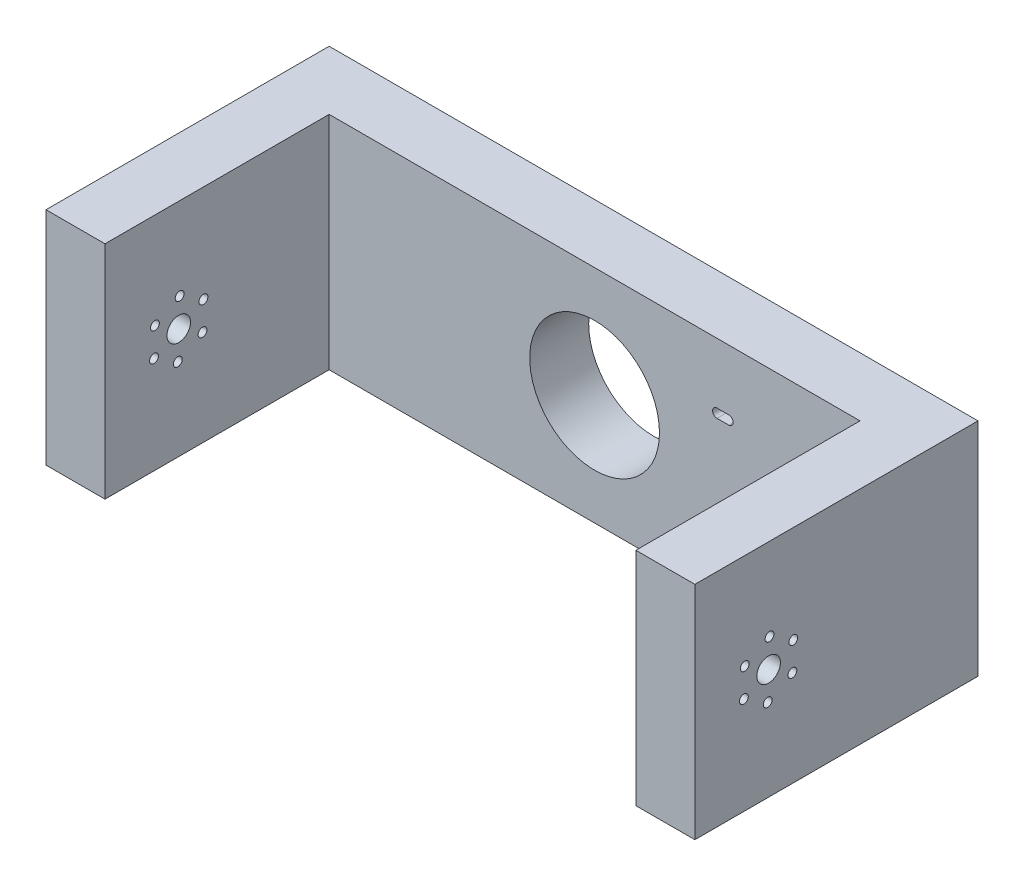
SolidWorks part; units mm, degrees
ref_plane "Front" through (0, 0, 0) normal (0, 0, 1) x (1, 0, 0)
ref_plane "Top" through (0, 0, 0) normal (0, 1, 0) x (1, 0, 0)
ref_plane "Right" through (0, 0, 0) normal (1, 0, 0) x (0, 0, -1)
sketch "Esquisse1" plane through (0, 0, 0) normal (0, 0, 1) x (1, 0, 0)
  line L1 (0, 0) -> (220, 0)
  line L2 (0, 0) -> (0, 75)
  line L3 (0, 75) -> (220, 75)
  line L4 (220, 0) -> (220, 75)
  dimension "D1" = 220
  dimension "D2" = 75
extrude "Boss.-Extru.1" add sketch "Esquisse1" along normal blind 20
sketch "Esquisse2" plane through (0, 0, 20) normal (0, 0, 1) x (1, 0, 0)
  line L0 (0, 0) -> (220, 0) construction
  line L1 (220, 75) -> (200, 75)
  line L2 (220, 75) -> (220, 0)
  line L3 (220, 0) -> (200, 0)
  line L4 (200, 75) -> (200, 0)
  line L6 (0, 75) -> (20, 75)
  line L7 (0, 75) -> (0, 0)
  line L8 (0, 0) -> (20, 0)
  line L9 (20, 75) -> (20, 0)
  dimension "D1" = 20
extrude "Boss.-Extru.2" add sketch "Esquisse2" along normal blind 76
sketch "Esquisse3" plane through (220, 0, 0) normal (1, 0, 0) x (0, 0, -1)
  line L0 (-96, 0) -> (-96, 75) construction
  line L1 (-96, 75) -> (0, 75) construction
  circle A0 centre (-71, 37.5) radius 4
  dimension "D1" = 8
  dimension "D2" = 25
  dimension "D3" = 37.5
extrude "Enlèv. mat.-Extru.1" cut sketch "Esquisse3" against normal through all
sketch "Esquisse4" plane through (0, 0, 20) normal (0, 0, 1) x (1, 0, 0)
  line L0 (220, 0) -> (220, 75) construction
  line L2 (200, 75) -> (20, 75) construction
  circle A0 centre (110, 37.5) radius 22
  dimension "D1" = 110
  dimension "D2" = 37.5
  dimension "D3" = 44
extrude "Enlèv. mat.-Extru.2" cut sketch "Esquisse4" against normal blind 76
sketch "Esquisse5" plane through (220, 0, 0) normal (1, 0, 0) x (0, 0, -1)
  circle A0 centre (-70.6855, 47) radius 1.5
  circle A1 centre (-71, 37.5) radius 4 construction
  circle A2 centre (-62.6155, 41.9776) radius 1.5
  circle A3 centre (-62.93, 32.4776) radius 1.5
  circle A4 centre (-71.3145, 28) radius 1.5
  circle A5 centre (-79.3845, 33.0224) radius 1.5
  circle A6 centre (-79.07, 42.5224) radius 1.5
  point P17 (-71, 37.5)
  dimension "D1" = 3
  dimension "D2" = 9.5
  dimension "D3" = 6
extrude "Enlèv. mat.-Extru.3" cut sketch "Esquisse5" against normal through all
sketch "Esquisse6" plane through (0, 0, 20) normal (0, 0, 1) x (1, 0, 0)
  line L0 (200, 75) -> (20, 75) construction
  line L1 (148, 58.5) -> (190, 58.5)
  line L2 (148, 58.5) -> (148, 16.5)
  line L3 (148, 16.5) -> (190, 16.5)
  line L4 (190, 58.5) -> (190, 16.5)
  line L5 (200, 75) -> (200, 0) construction
  line L6 (182.5, 53) -> (186.5, 53) construction
  line L9 (182.5, 54.5) -> (186.5, 54.5)
  line L10 (182.5, 51.5) -> (186.5, 51.5)
  line L11 (151.5, 51.5) -> (155.5, 51.5)
  line L12 (151.5, 54.5) -> (155.5, 54.5)
  line L13 (151.5, 53) -> (155.5, 53) construction
  line L14 (151.5, 20.5) -> (155.5, 20.5)
  line L15 (151.5, 23.5) -> (155.5, 23.5)
  line L16 (151.5, 22) -> (155.5, 22) construction
  line L17 (182.5, 20.5) -> (186.5, 20.5)
  line L18 (182.5, 23.5) -> (186.5, 23.5)
  line L19 (182.5, 22) -> (186.5, 22) construction
  circle A0 centre (153.5, 53) radius 1.5
  circle A1 centre (184.5, 53) radius 1.5
  circle A2 centre (184.5, 22) radius 1.5
  circle A3 centre (153.5, 22) radius 1.5
  arc A6 (182.5, 54.5) -> (182.5, 51.5) centre (182.5, 53) ccw
  arc A7 (186.5, 51.5) -> (186.5, 54.5) centre (186.5, 53) ccw
  arc A8 (151.5, 54.5) -> (151.5, 51.5) centre (151.5, 53) ccw
  arc A9 (155.5, 51.5) -> (155.5, 54.5) centre (155.5, 53) ccw
  arc A10 (151.5, 23.5) -> (151.5, 20.5) centre (151.5, 22) ccw
  arc A11 (155.5, 20.5) -> (155.5, 23.5) centre (155.5, 22) ccw
  arc A12 (182.5, 23.5) -> (182.5, 20.5) centre (182.5, 22) ccw
  arc A13 (186.5, 20.5) -> (186.5, 23.5) centre (186.5, 22) ccw
  point P12 (184.5, 53)
  point P28 (153.5, 53)
  point P35 (153.5, 22)
  point P42 (184.5, 22)
  dimension "D4" = 3
  dimension "D5" = 5.5
  dimension "D6" = 5.5
  dimension "D9" = 4
  dimension "D10" = 1.5
  dimension "D11" = 31
  dimension "D12" = 31
  dimension "D13" = 2
  dimension "D1" = 42
  dimension "D2" = 16.5
  dimension "D3" = 10
  dimension "D7" = 2
  dimension "D8" = 2
  dimension "D14" = 2
extrude "Enlèv. mat.-Extru.5" cut sketch "Esquisse6" against normal through all contours L11 A9 L12 A0 | L12 A8 L11 A0 | L10 A7 L9 A1 | L9 A6 L10 A1 | A1 | L17 A13 L18 A2 | A2 | L18 A12 L17 A2 | A3 | L14 A11 L15 A3 | L15 A10 L14 A3 | A0 L1
